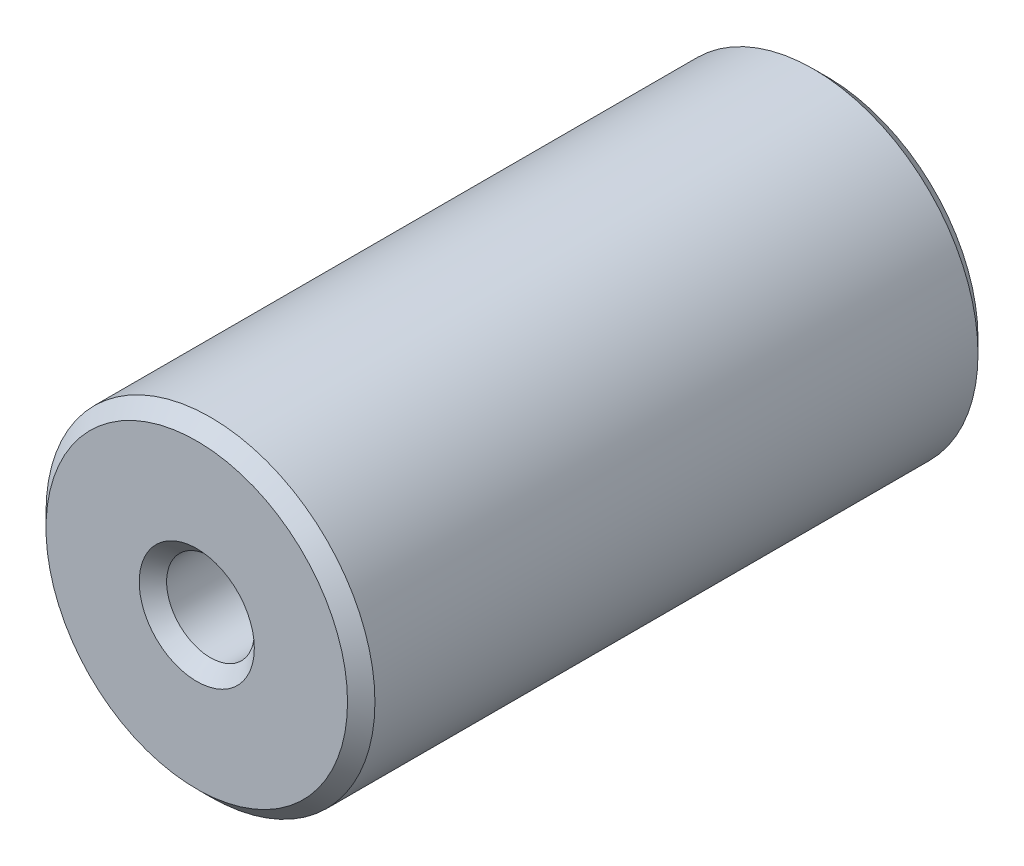
SolidWorks part; units mm, degrees
ref_plane "Plan de face" through (0, 0, 0) normal (0, 0, 1) x (1, 0, 0)
ref_plane "Plan de dessus" through (0, 0, 0) normal (0, 1, 0) x (1, 0, 0)
ref_plane "Plan de droite" through (0, 0, 0) normal (1, 0, 0) x (0, 0, -1)
sketch "Esquisse1" plane through (0, 0, 0) normal (0, 0, 1) x (1, 0, 0)
  circle A0 centre (0, 0) radius 3.2
  circle A1 centre (0, 0) radius 12
  dimension "D1" = 6.4
  dimension "D2" = 24
extrude "Boss.-Extru.1" add sketch "Esquisse1" along normal blind 46
chamfer "Chanfrein1" distance 1 angle 45 4 edges at (3.2, 0, 0) (3.2, 0, 46) (12, 0, 0) (12, 0, 46)
